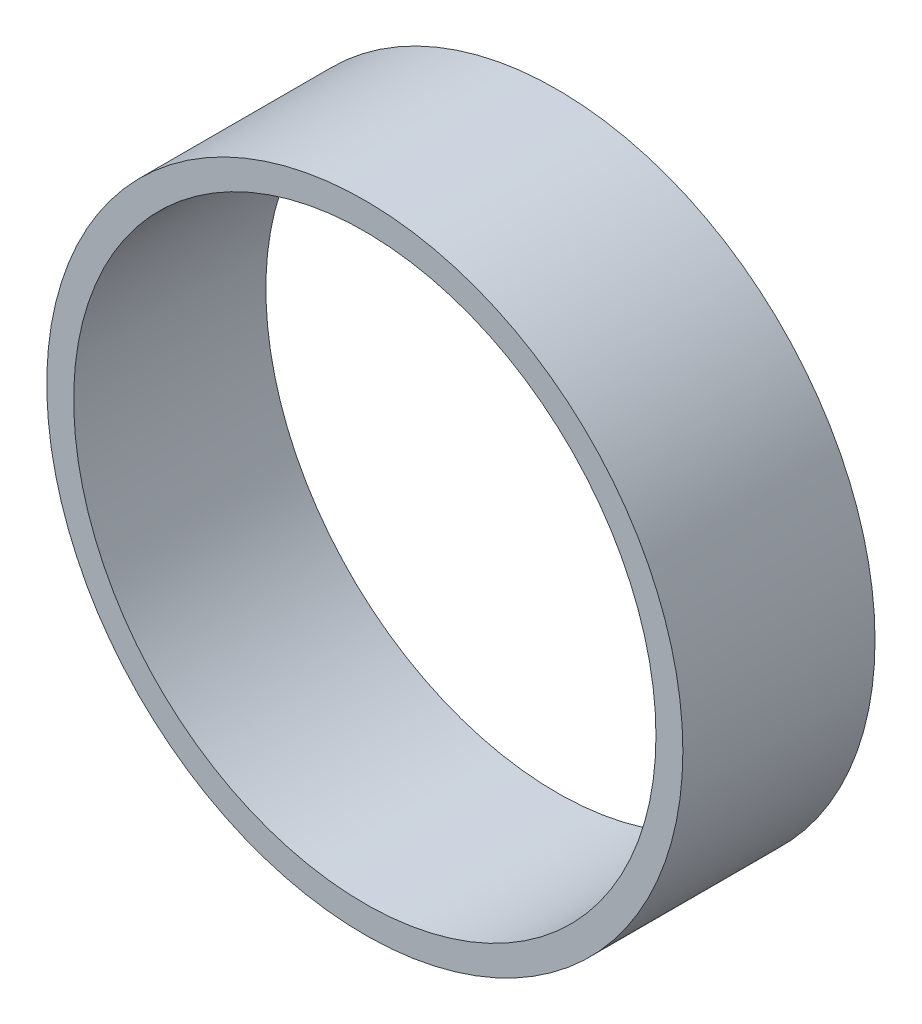
SolidWorks part; units mm, degrees
ref_plane "Front" through (0, 0, 0) normal (0, 0, 1) x (1, 0, 0)
ref_plane "Top" through (0, 0, 0) normal (0, 1, 0) x (1, 0, 0)
ref_plane "Side" through (0, 0, 0) normal (1, 0, 0) x (0, 0, -1)
other "Configuration Table"
sketch "PipeSketch" plane through (0, 0, 0) normal (0, 0, 1) x (1, 0, 0)
  circle A0 centre (0, 0) radius 84.074
  circle A1 centre (0, 0) radius 76.962
  dimension "OuterDiameter" = 168.148
  dimension "InnerDiameter" = 153.924
extrude "Extrusion" add sketch "PipeSketch" along normal blind 50.8
sketch "FilterSketch" plane through (0, 0, 0) normal (0, 0, 1) x (1, 0, 0)
  circle A0 centre (0, 0) radius 76.2 construction
  dimension "NominalDiameter" = 152.4
